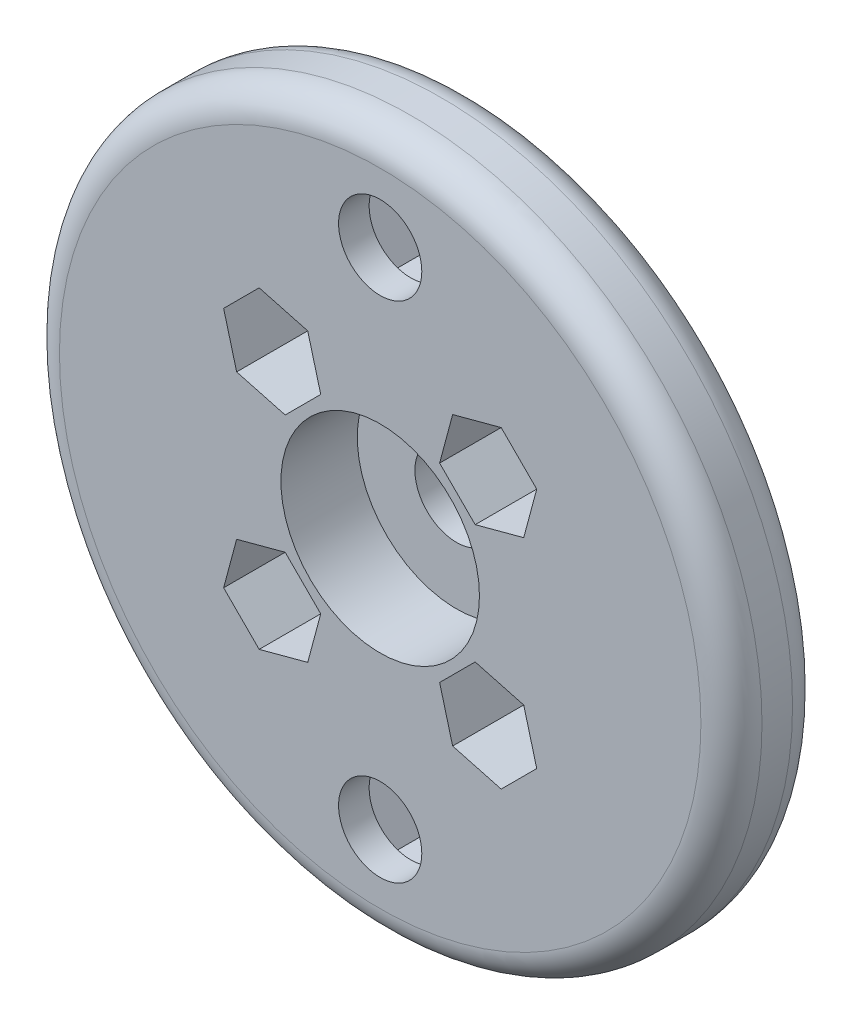
SolidWorks part; units mm, degrees
material "ABS"
ref_plane "Front Plane" through (0, 0, 0) normal (0, 0, 1) x (1, 0, 0)
ref_plane "Top Plane" through (0, 0, 0) normal (0, 1, 0) x (1, 0, 0)
ref_plane "Right Plane" through (0, 0, 0) normal (1, 0, 0) x (0, 0, -1)
sketch "Sketch1" plane through (0, 0, 0) normal (0, 0, 1) x (1, 0, 0)
  circle A0 centre (0, 0) radius 23
  dimension "D1" = 46
extrude "Boss-Extrude3" add sketch "Sketch1" along normal blind 10
sketch "Sketch3" plane through (0, 0, 0) normal (0, 0, -1) x (-1, 0, 0)
  circle A0 centre (0, 0) radius 13
  circle A1 centre (0, 0) radius 23 construction
  circle A2 centre (0, 0) radius 23
  dimension "D1" = 26
extrude "Cut-Extrude1" cut sketch "Sketch3" against normal blind 4
sketch "Sketch4" plane through (0, 0, 0) normal (0, 0, -1) x (-1, 0, 0)
  line L0 (-9.1924, 9.1924) -> (9.1924, -9.1924) construction
  line L1 (-7.0711, -7.0711) -> (7.0711, 7.0711) construction
  line L2 (0, 10) -> (0, -10) construction
  circle A0 centre (-7.0711, -7.0711) radius 1.725
  circle A1 centre (7.0711, 7.0711) radius 1.725
  circle A2 centre (0, 0) radius 2.725
  circle A3 centre (0, 0) radius 13 construction
  circle A4 centre (0, 0) radius 13 construction
  circle A5 centre (0, 0) radius 10 construction
  circle A6 centre (-7.0711, 7.0711) radius 1.725
  circle A7 centre (7.0711, -7.0711) radius 1.725
  dimension "D2" = 3.45
  dimension "D3" = 5.45
  dimension "D1" = 20
  dimension "D4" = 45
extrude "Cut-Extrude2" cut sketch "Sketch4" against normal through all
sketch "Sketch5" plane through (0, 0, 10) normal (0, 0, 1) x (1, 0, 0)
  line L0 (-7.0711, 7.0711) -> (7.0711, -7.0711) construction
  line L1 (-7.9228, 10.2498) -> (-10.2498, 7.9228)
  line L2 (-10.2498, 7.9228) -> (-9.3981, 4.7441)
  line L3 (-9.3981, 4.7441) -> (-6.2193, 3.8923)
  line L4 (-6.2193, 3.8923) -> (-3.8923, 6.2193)
  line L5 (-3.8923, 6.2193) -> (-4.7441, 9.3981)
  line L6 (-4.7441, 9.3981) -> (-7.9228, 10.2498)
  line L7 (9.3981, -4.7441) -> (6.2193, -3.8923)
  line L8 (6.2193, -3.8923) -> (3.8923, -6.2193)
  line L9 (3.8923, -6.2193) -> (4.7441, -9.3981)
  line L10 (4.7441, -9.3981) -> (7.9228, -10.2498)
  line L11 (7.9228, -10.2498) -> (10.2498, -7.9228)
  line L12 (10.2498, -7.9228) -> (9.3981, -4.7441)
  line L14 (-3.8923, -6.2193) -> (-6.2193, -3.8923)
  line L15 (-6.2193, -3.8923) -> (-9.3981, -4.7441)
  line L16 (-9.3981, -4.7441) -> (-10.2498, -7.9228)
  line L17 (-10.2498, -7.9228) -> (-7.9228, -10.2498)
  line L18 (-7.9228, -10.2498) -> (-4.7441, -9.3981)
  line L19 (-4.7441, -9.3981) -> (-3.8923, -6.2193)
  line L20 (9.3981, 4.7441) -> (10.2498, 7.9228)
  line L21 (10.2498, 7.9228) -> (7.9228, 10.2498)
  line L22 (7.9228, 10.2498) -> (4.7441, 9.3981)
  line L23 (4.7441, 9.3981) -> (3.8923, 6.2193)
  line L24 (3.8923, 6.2193) -> (6.2193, 3.8923)
  line L25 (6.2193, 3.8923) -> (9.3981, 4.7441)
  circle A0 centre (0, 0) radius 6.5
  circle A1 centre (-7.0711, 7.0711) radius 2.85 construction
  circle A2 centre (7.0711, -7.0711) radius 2.85 construction
  circle A3 centre (-7.0711, -7.0711) radius 2.85 construction
  circle A4 centre (7.0711, 7.0711) radius 2.85 construction
  dimension "D1" = 13
  dimension "D2" = 5.7
extrude "Cut-Extrude3" cut sketch "Sketch5" against normal blind 5
sketch "Sketch6" plane through (0, 0, 10) normal (0, 0, 1) x (1, 0, 0)
  line L0 (-23, 0) -> (23, 0) construction
  circle A0 centre (0, 16.5) radius 2.725
  circle A1 centre (0, -16.5) radius 2.725
  circle A2 centre (0, 0) radius 23 construction
  dimension "D2" = 5.45
  dimension "D1" = 33
extrude "Cut-Extrude4" cut sketch "Sketch6" against normal through all
sketch "Sketch7" plane through (0, 0, 4) normal (0, 0, -1) x (-1, 0, 0)
  line L1 (4.7343, 16.5) -> (2.3671, 20.6)
  line L2 (2.3671, 20.6) -> (-2.3671, 20.6)
  line L3 (-2.3671, 20.6) -> (-4.7343, 16.5)
  line L4 (-4.7343, 16.5) -> (-2.3671, 12.4)
  line L5 (-2.3671, 12.4) -> (2.3671, 12.4)
  line L6 (2.3671, 12.4) -> (4.7343, 16.5)
  line L7 (4.7343, -16.5) -> (2.3671, -12.4)
  line L8 (2.3671, -12.4) -> (-2.3671, -12.4)
  line L9 (-2.3671, -12.4) -> (-4.7343, -16.5)
  line L10 (-4.7343, -16.5) -> (-2.3671, -20.6)
  line L11 (-2.3671, -20.6) -> (2.3671, -20.6)
  line L12 (2.3671, -20.6) -> (4.7343, -16.5)
  circle A0 centre (0, 16.5) radius 4.1 construction
  circle A1 centre (0, -16.5) radius 4.1 construction
  dimension "D1" = 8.2
extrude "Cut-Extrude5" cut sketch "Sketch7" against normal blind 4 and the other way through all
fillet "Fillet1" radius 2 4 edges at (13, 0, 4) (-13, 0, 4) (-23, 0, 4) (23, 0, 10)
equation "\"D2@Sketch4\"=3.00mm+\"print_free@Parameters@Parameters.SLDPRT\""
equation "\"D3@Sketch4\"=5.00mm+\"print_free@Parameters@Parameters.SLDPRT\""
equation "\"D2@Sketch5\"=5.50mm+\"print_fit@Parameters@Parameters.SLDPRT\""
equation "\"D2@Sketch6\"=5.00mm+\"print_free@Parameters@Parameters.SLDPRT\""
equation "\"D1@Sketch7\"=8.00mm+\"print_fit@Parameters@Parameters.SLDPRT\""
